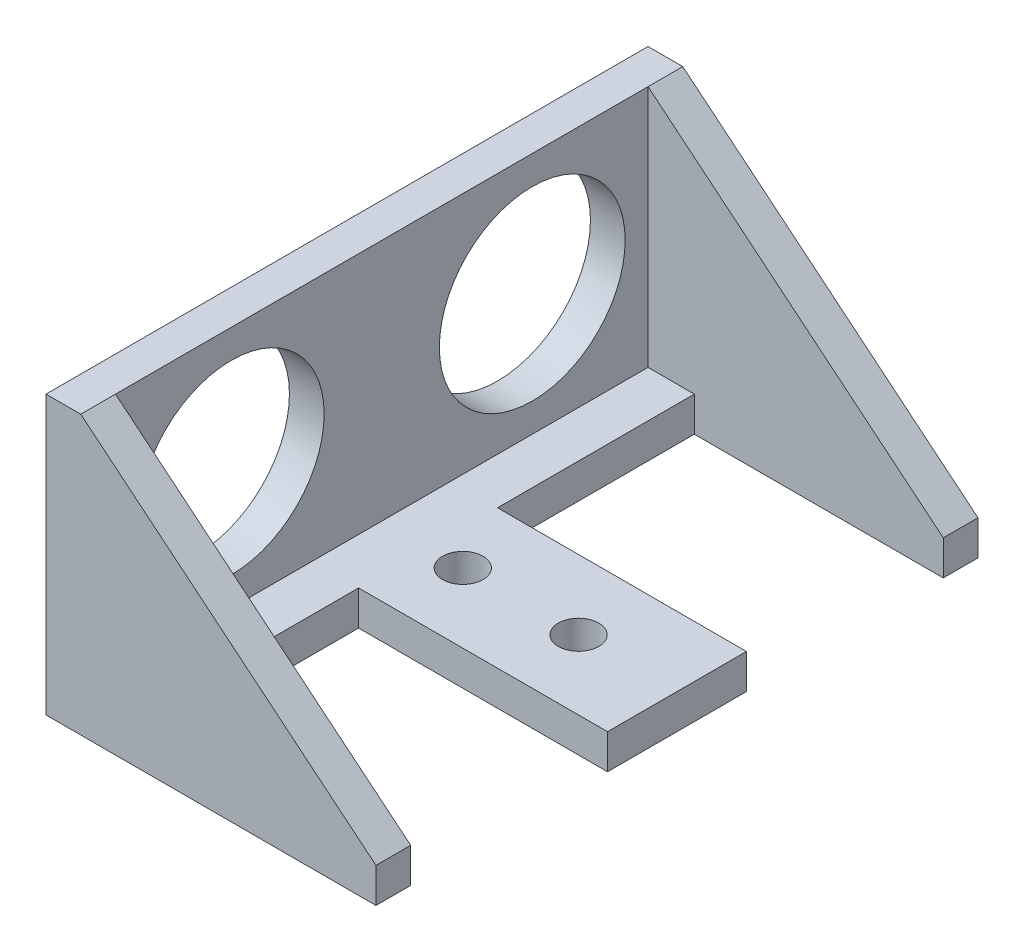
SolidWorks part; units mm, degrees
ref_plane "Alzado" through (0, 0, 0) normal (0, 0, 1) x (1, 0, 0)
ref_plane "Planta" through (0, 0, 0) normal (0, 1, 0) x (1, 0, 0)
ref_plane "Vista lateral" through (0, 0, 0) normal (1, 0, 0) x (0, 0, -1)
sketch "Croquis1" plane through (0, 0, 0) normal (1, 0, 0) x (0, 0, -1)
  line L0 (0, 0) -> (26, 0) construction
  line L2 (-13, 10.5) -> (39, 10.5)
  line L3 (-13, 10.5) -> (-13, -10.5)
  line L4 (-13, -10.5) -> (39, -10.5)
  line L5 (39, 10.5) -> (39, -10.5)
  circle A0 centre (0, 0) radius 8.025
  circle A1 centre (26, 0) radius 8.025
  point P9 (-14.9572, -13.056)
  point P10 (-13, 0)
  point P11 (-14.312, 10.5)
  point P12 (13, 0)
  point P13 (13, 10.5)
  point P14 (36.4434, -10.5)
  dimension "D2" = 16.05
  dimension "D1" = 26
  dimension "D3" = 21
  dimension "D4" = 52
extrude "Saliente-Extruir1" add sketch "Croquis1" along normal blind 3
sketch "Croquis2" plane through (0, 0, 0) normal (-1, 0, 0) x (0, 0, 1)
  line L1 (-39, -10.5) -> (13, -10.5)
  line L2 (-39, -10.5) -> (-39, -13.5)
  line L3 (-39, -13.5) -> (13, -13.5)
  line L4 (13, -10.5) -> (13, -13.5)
  line L5 (13, 10.5) -> (10, 10.5)
  line L6 (13, 10.5) -> (13, -10.5)
  line L7 (13, -10.5) -> (10, -10.5)
  line L8 (10, 10.5) -> (10, -10.5)
  line L9 (-39, 10.5) -> (-36, 10.5)
  line L10 (-39, 10.5) -> (-39, -10.5)
  line L11 (-39, -10.5) -> (-36, -10.5)
  line L12 (-36, 10.5) -> (-36, -10.5)
  line M6 (13, -10.5) -> (13, 10.5)
  line M7 (13, 10.5) -> (-39, 10.5)
  line M9 (-39, -10.5) -> (13, -10.5)
  dimension "D1" = 3
extrude "Saliente-Extruir2" add sketch "Croquis2" against normal blind 28.5 contours L4 L1 L2 L3 M9 | L8 L1 M7 M6 | L11 L12 L9 L10
sketch "Croquis3" plane through (0, 0, 13) normal (0, 0, 1) x (1, 0, 0)
  line L0 (3, 10.5) -> (28.5, -10.5)
  line L1 (28.5, 10.5) -> (0, 10.5) construction
  line L2 (28.5, 10.5) -> (28.5, -13.5) construction
  line L3 (28.5, -10.5) -> (28.5, 10.5)
  line L4 (28.5, 10.5) -> (3, 10.5)
  line L5 (0, 10.5) -> (0, -13.5) construction
  line L6 (28.5, -13.5) -> (0, -13.5) construction
  dimension "D1" = 3
  dimension "D2" = 3
extrude "Cortar-Extruir1" cut sketch "Croquis3" against normal through all
sketch "Croquis4" plane through (0, -10.5, 0) normal (0, 1, 0) x (1, 0, 0)
  line L0 (0, 39) -> (0, -13) construction
  circle A0 centre (10, 13) radius 1.75
  circle A1 centre (20, 13) radius 1.75
  point P6 (0, 13)
  point P7 (0, 0)
  dimension "D3" = 3.5
  dimension "D1" = 10
  dimension "D2" = 10
extrude "Cortar-Extruir2" cut sketch "Croquis4" against normal through all
sketch "Croquis5" plane through (0, -10.5, 0) normal (0, 1, 0) x (1, 0, 0)
  line L0 (28.5, 39) -> (0, 39) construction
  line L1 (7, 36) -> (28.5, 36)
  line L2 (7, 36) -> (7, 19)
  line L3 (7, 19) -> (28.5, 19)
  line L4 (28.5, 36) -> (28.5, 19)
  line L5 (28.5, 39) -> (28.5, -13) construction
  line L6 (0, 39) -> (0, -13) construction
  line L7 (0, 13) -> (28.5, 13) construction
  line L8 (7, 7) -> (28.5, 7)
  line L9 (28.5, -10) -> (28.5, 7)
  line L10 (7, -10) -> (7, 7)
  line L11 (7, -10) -> (28.5, -10)
  point P16 (26.9544, 37.4476)
  dimension "D1" = 7
  dimension "D2" = 20
  dimension "D3" = 3
extrude "Cortar-Extruir3" cut sketch "Croquis5" against normal through all
